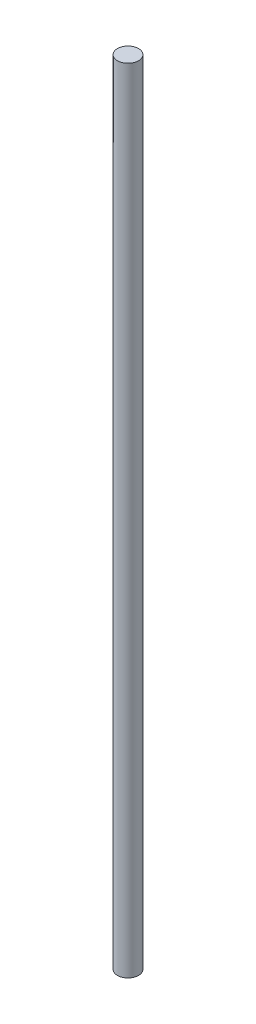
SolidWorks part; units mm, degrees
ref_plane "Front Plane" through (0, 0, 0) normal (0, 0, 1) x (1, 0, 0)
ref_plane "Top Plane" through (0, 0, 0) normal (0, 1, 0) x (1, 0, 0)
ref_plane "Right Plane" through (0, 0, 0) normal (1, 0, 0) x (0, 0, -1)
sketch "Sketch1" plane through (0, 0, 0) normal (0, 1, 0) x (1, 0, 0)
  circle A0 centre (0, 0) radius 10
  dimension "D1" = 20
extrude "Boss-Extrude1" add sketch "Sketch1" along normal mid plane 750
